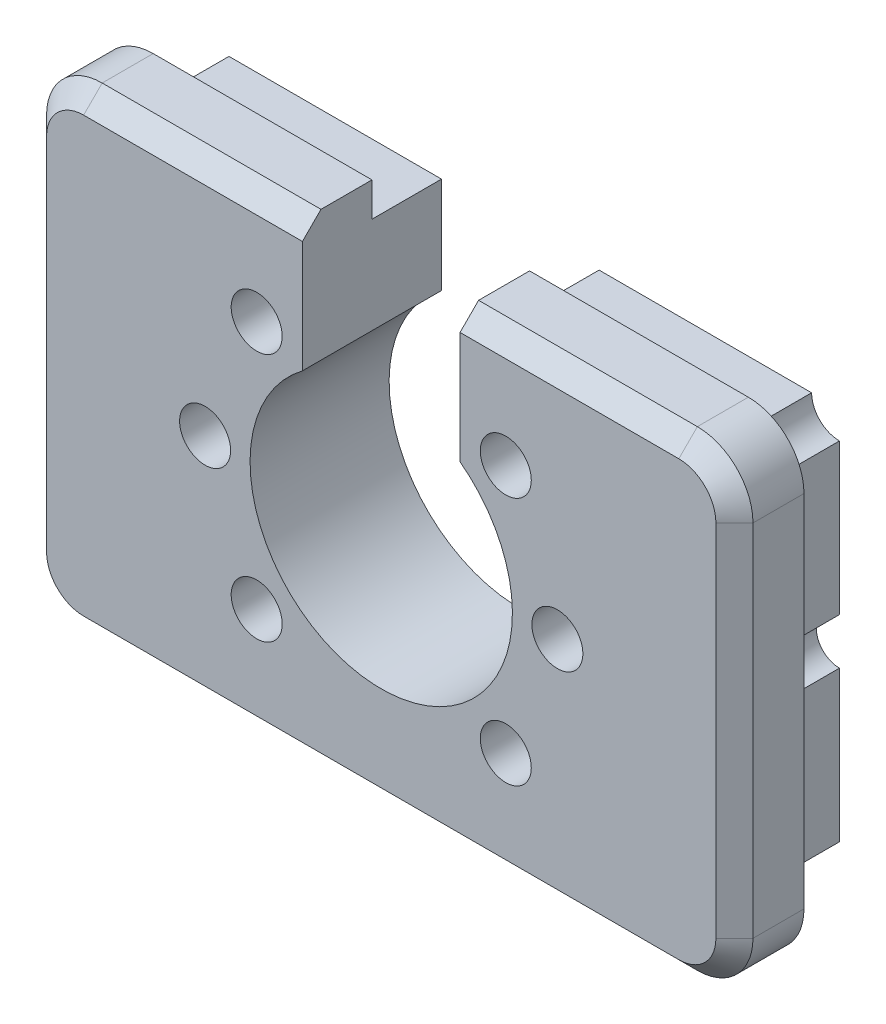
SolidWorks part; units mm, degrees
material "PET"
ref_plane "Front Plane" through (0, 0, 0) normal (0, 0, 1) x (1, 0, 0)
ref_plane "Top Plane" through (0, 0, 0) normal (0, 1, 0) x (1, 0, 0)
ref_plane "Right Plane" through (0, 0, 0) normal (1, 0, 0) x (0, 0, -1)
sketch "Sketch1" plane through (0, 0, 0) normal (0, 0, 1) x (1, 0, 0)
  line L1 (38.1, -25.4) -> (-38.1, -25.4)
  line L2 (38.1, -25.4) -> (38.1, 25.4)
  line L3 (38.1, 25.4) -> (-38.1, 25.4)
  line L4 (-38.1, -25.4) -> (-38.1, 25.4)
  line L5 (38.1, -25.4) -> (-38.1, 25.4) construction
  line L6 (38.1, 25.4) -> (-38.1, -25.4) construction
  point P0 (0, 0)
  dimension "D1" = 50.8
  dimension "D2" = 76.2
extrude "Boss-Extrude1" add sketch "Sketch1" against normal blind 7.5
sketch "Sketch2" plane through (0, 0, -7.5) normal (0, 0, -1) x (-1, 0, 0)
  line L8 (34.425, -21.725) -> (34.425, 21.725)
  line L9 (34.425, 21.725) -> (-34.425, 21.725)
  line L10 (-34.425, 21.725) -> (-34.425, -21.725)
  line L11 (-34.425, -21.725) -> (34.425, -21.725)
  line L12 (34.425, -21.725) -> (34.425, 21.725)
  line L13 (34.425, 21.725) -> (-34.425, 21.725)
  line L14 (-34.425, 21.725) -> (-34.425, -21.725)
  line L15 (-34.425, -21.725) -> (34.425, -21.725)
  dimension "D1" = 3.675
extrude "Boss-Extrude2" add sketch "Sketch2" along normal blind 7.5
sketch "Sketch3" plane through (0, 0, 0) normal (0, 0, 1) x (1, 0, 0)
  line L0 (0, 0) -> (0, 51.1675) construction
  line L1 (38.1, 25.4) -> (-38.1, 25.4) construction
  line L2 (8.5, 11.3125) -> (-8.5, 11.3125) construction
  line L3 (8.5, 11.3125) -> (8.5, 25.4)
  line L4 (8.5, 25.4) -> (-8.5, 25.4)
  line L5 (-8.5, 11.3125) -> (-8.5, 25.4)
  line L6 (8.5, 11.3125) -> (-8.5, 25.4) construction
  line L7 (8.5, 25.4) -> (-8.5, 11.3125) construction
  line L8 (0, 0) -> (-19, 0) construction
  arc A0 (-8.5, 11.3125) -> (8.5, 11.3125) centre (0, 0) ccw
  circle A1 centre (-19, 0) radius 2.75
  circle A2 centre (-13.435, 13.435) radius 2.75
  circle A3 centre (0, 19) radius 2.75 construction
  circle A4 centre (13.435, 13.435) radius 2.75
  circle A5 centre (19, 0) radius 2.75
  circle A6 centre (13.435, -13.435) radius 2.75
  circle A7 centre (0, -19) radius 2.75 construction
  circle A8 centre (-13.435, -13.435) radius 2.75
  point P3 (0, 18.3562)
  point P28 (0, 0)
  dimension "D1" = 28.3
  dimension "D4" = 5.5
  dimension "D2" = 17
  dimension "D3" = 19
  dimension "D5" = 8
extrude "Cut-Extrude1" cut sketch "Sketch3" against normal through all
fillet "Fillet1" radius 6 4 edges at (38.1, -25.4, -3.75) (-38.1, -25.4, -3.75) (-38.1, 25.4, -3.75) (38.1, 25.4, -3.75)
sketch "Sketch4" plane through (0, 0, -15) normal (0, 0, -1) x (-1, 0, 0)
  line L0 (-34.425, 21.725) -> (-34.425, -21.725) construction
  line L5 (-34.425, -21.725) -> (0, -21.725) construction
  line L6 (0, 0) -> (0, -21.725) construction
  circle A0 centre (-34.425, 21.725) radius 3
  circle A1 centre (-34.425, -21.725) radius 3
  circle A2 centre (-34.425, 0) radius 2.5
  circle A3 centre (0, -21.725) radius 2.5
  circle A4 centre (34.425, -21.725) radius 3
  circle A5 centre (34.425, 0) radius 2.5
  circle A6 centre (34.425, 21.725) radius 3
  arc A7 (-32.1, 25.4) -> (-38.1, 19.4) centre (-32.1, 19.4) ccw construction
  arc A8 (-32.1, 25.4) -> (-38.1, 19.4) centre (-32.1, 19.4) ccw construction
  dimension "D4" = 5
  dimension "D5" = 6
  dimension "D1" = 6
extrude "Cut-Extrude2" cut sketch "Sketch4" against normal up to surface (7.5 mm away) up to face at (0, 5.8906, -7.5)
chamfer "Chamfer1" distance 2 angle 45 9 edges at (-20.3, 25.4, 0) (-36.3426, 23.6426, 0) (-38.1, 0, 0) (-36.3426, -23.6426, 0) (0, -25.4, 0) (36.3426, -23.6426, 0) (38.1, 0, 0) (36.3426, 23.6426, 0) (20.3, 25.4, 0)
chamfer "Chamfer2" [suppressed] distance 3 angle 45
equation "\"hole_radius\"= 14.15mm"
equation "\"D1@Sketch3\"=\"hole_radius\"*2"
equation "\"M5_tap\"=4.2mm\t\t\t\t\t\t\t' Below you can do mesurements as follows: cm, mm, ft, in, m, "
equation "\"M5_clearence\"=5.5mm"
equation "\"M6_tap\"=5mm"
equation "\"M6_clearence\"=6.6mm"
equation "\"work_area_width\"=1100mm"
equation "\"work_area_depth\"=900mm"
equation "\"steel_base_width\"=3in\t"
equation "\"steel_base_height\"=2in"
equation "\"steel_base_wall_thickness\"=0.125in"
equation "\"steel_base_radius\"=6mm"
equation "\"steel_sides_width\"=3in\t\t\t\t\t'this tube is rotated so flip width/height"
equation "\"steel_sides_height\"=2in\t\t\t\t'this tube is rotated so flip width/height"
equation "\"steel_sides_wall_thickness\"=0.125in"
equation "\"steel_sides_radius\"=6mm"
equation "\"steel_gantry_width\"=4in\t\t\t\t'this tube is rotated so flip width/height"
equation "\"steel_gantry_height\"=3in\t\t\t\t'this tube is rotated so flip width/height"
equation "\"steel_gantry_wall_thickness\"=0.125in"
equation "\"steel_gantry_radius\"=6mm"
equation "\"steel_rollers_width\"=3in"
equation "\"steel_rollers_height\"=2in\t\t\t\t'keep as low as possible as this increases how big plastic parts are"
equation "\"steel_rollers_wall_thickness\"=0.125in"
equation "\"steel_rollers_radius\"=6mm"
equation "\"steel_zbox_width\"=4in\t\t\t\t\t'if the gantry height (rotated) is too thick, a wider zbox is necessary"
equation "\"steel_zbox_height\"=2in\t\t\t\t\t'hole patteren changes as the zbox and gantry height (rotated) changes."
equation "\"steel_zbox_wall_thickness\"=0.125in"
equation "\"steel_zbox_radius\"=6mm"
equation "\"D2@Sketch1\"=\"steel_rollers_width\""
equation "\"D1@Sketch1\"=\"steel_rollers_height\""
equation "\"D1@Sketch2\"=\"steel_rollers_wall_thickness\" + 0.5mm"
equation "\"D5@Sketch4\"=\"D1@Sketch4\""
